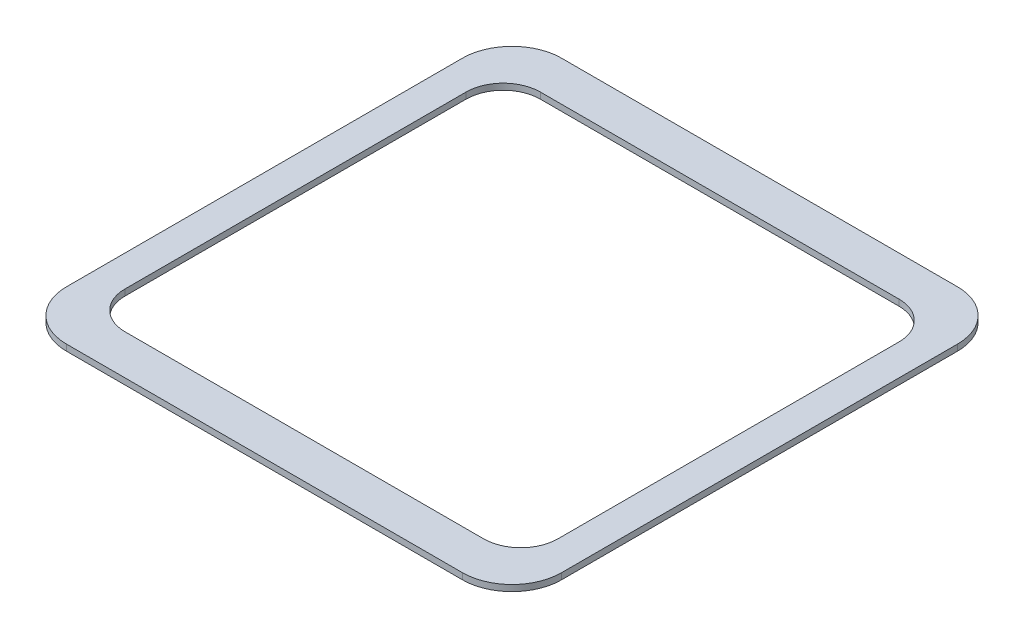
SolidWorks part; units mm, degrees
ref_plane "Front Plane" through (0, 0, 0) normal (0, 0, 1) x (1, 0, 0)
ref_plane "Top Plane" through (0, 0, 0) normal (0, 1, 0) x (1, 0, 0)
ref_plane "Right Plane" through (0, 0, 0) normal (1, 0, 0) x (0, 0, -1)
sketch "Sketch2" plane through (0, -3.4417, 0) normal (0, -1, 0) x (-1, 0, 0)
  line L21 (-50.8, 63.5) -> (50.8, 63.5)
  line L22 (63.5, 50.8) -> (63.5, -50.8)
  line L23 (-50.8, -63.5) -> (50.8, -63.5)
  line L24 (-63.5, 50.8) -> (-63.5, -50.8)
  line L39 (45.9922, 53.2625) -> (-45.9922, 53.2625)
  line L40 (-55.5159, 43.7388) -> (-55.5159, -43.7388)
  line L41 (-45.9922, -53.2625) -> (45.9922, -53.2625)
  line L42 (55.5159, -43.7388) -> (55.5159, 0)
  line L43 (55.5159, 0) -> (55.5159, 43.7388)
  line L44 (45.9922, 53.2625) -> (-45.9922, 53.2625)
  line L45 (-55.5159, 43.7388) -> (-55.5159, -43.7388)
  line L46 (-45.9922, -53.2625) -> (45.9922, -53.2625)
  line L47 (55.5159, -43.7388) -> (55.5159, 0)
  line L48 (55.5159, 0) -> (55.5159, 43.7388)
  arc A2 (-63.5, -50.8) -> (-50.8, -63.5) centre (-50.8, -50.8) ccw
  arc A17 (50.8, -63.5) -> (63.5, -50.8) centre (50.8, -50.8) ccw
  arc A18 (63.5, 50.8) -> (50.8, 63.5) centre (50.8, 50.8) ccw
  arc A19 (-50.8, 63.5) -> (-63.5, 50.8) centre (-50.8, 50.8) ccw
  arc A33 (55.5159, 43.7388) -> (45.9922, 53.2625) centre (45.9922, 43.7388) ccw
  arc A34 (-45.9922, 53.2625) -> (-55.5159, 43.7388) centre (-45.9922, 43.7388) ccw
  arc A35 (-55.5159, -43.7388) -> (-45.9922, -53.2625) centre (-45.9922, -43.7388) ccw
  arc A36 (45.9922, -53.2625) -> (55.5159, -43.7388) centre (45.9922, -43.7388) ccw
  arc A37 (55.5159, 43.7388) -> (45.9922, 53.2625) centre (45.9922, 43.7388) ccw
  arc A38 (-45.9922, 53.2625) -> (-55.5159, 43.7388) centre (-45.9922, 43.7388) ccw
  arc A39 (-55.5159, -43.7388) -> (-45.9922, -53.2625) centre (-45.9922, -43.7388) ccw
  arc A40 (45.9922, -53.2625) -> (55.5159, -43.7388) centre (45.9922, -43.7388) ccw
  dimension "D1" = 1.5875
extrude "MainBody" add sketch "Sketch2" along normal blind 1.5875
equation "\"ClampDepth\"= 3 / 8in"
equation "\"D1@Sketch2\"=0.0625"
